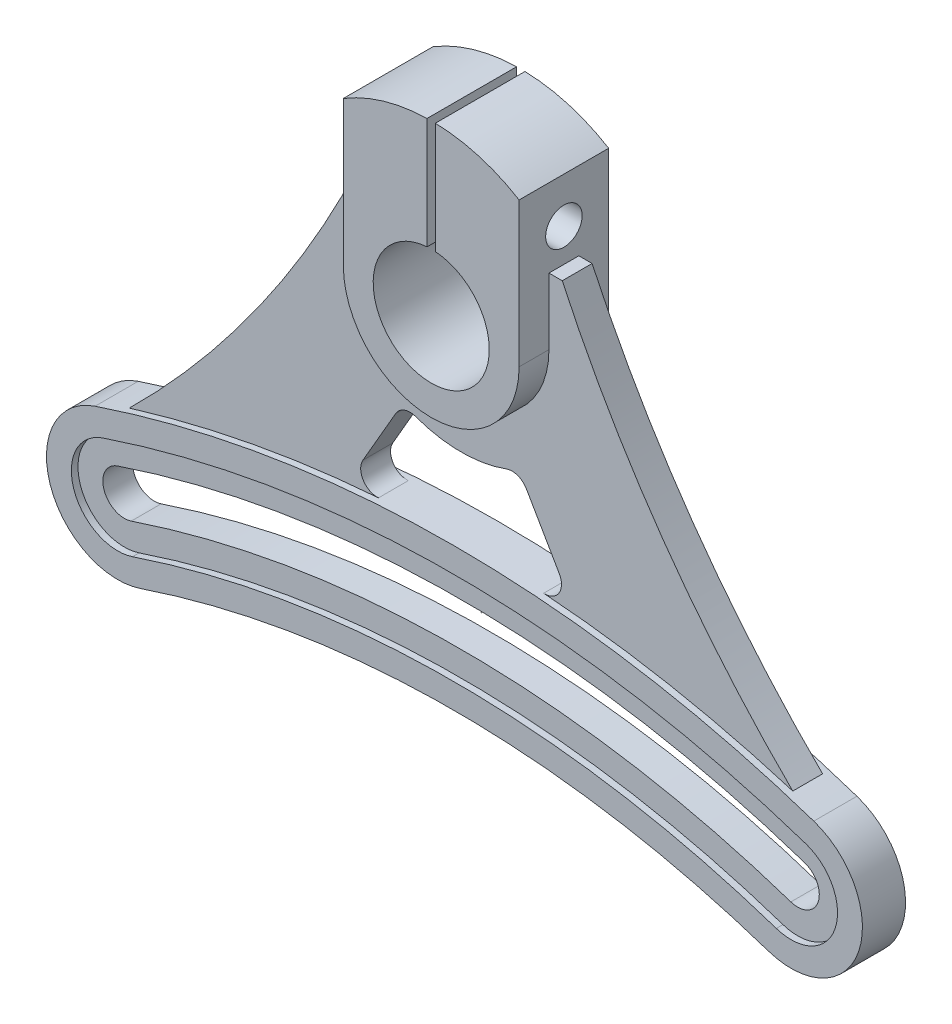
SolidWorks part; units mm, degrees
ref_plane "前视基准面" through (0, 0, 0) normal (0, 0, 1) x (1, 0, 0)
ref_plane "上视基准面" through (0, 0, 0) normal (0, 1, 0) x (1, 0, 0)
ref_plane "右视基准面" through (0, 0, 0) normal (1, 0, 0) x (0, 0, -1)
sketch "草图1" plane through (0, 0, 0) normal (0, 0, 1) x (1, 0, 0)
  line L0 (-26.5, 0) -> (-26.5, 43.5746)
  line L1 (26.5, 0) -> (26.5, 43.5746)
  circle A0 centre (0, 0) radius 17.5
  arc A1 (-26.5, 0) -> (26.5, 0) centre (0, 0) ccw
  arc A2 (26.5, 43.5746) -> (-26.5, 43.5746) centre (0, 0) ccw
  dimension "D1" = 35
  dimension "D2" = 102
  dimension "D3" = 53
extrude "凸台-拉伸1" add sketch "草图1" along normal mid plane 27
sketch "草图2" plane through (0, 0, 13.5) normal (0, 0, 1) x (1, 0, 0)
  line L0 (0, 0) -> (0, 70.8005) construction
  line L1 (-1.25, 64.567) -> (1.25, 64.567)
  line L2 (-1.25, 64.567) -> (-1.25, 8.1685)
  line L3 (-1.25, 8.1685) -> (1.25, 8.1685)
  line L4 (1.25, 64.567) -> (1.25, 8.1685)
  dimension "D1" = 2.5
extrude "切除-拉伸1" cut sketch "草图2" against normal through all
sketch "草图3" plane through (-26.5, 0, 0) normal (-1, 0, 0) x (0, 0, 1)
  line L0 (0, 50.9847) -> (0, 29.9847) construction
  line L1 (13.5, 50.9847) -> (-13.5, 50.9847) construction
  circle A0 centre (0, 29.9847) radius 5.5
  dimension "D2" = 11
  dimension "D1" = 21
extrude "切除-拉伸2" cut sketch "草图3" against normal through all
sketch "草图4" plane through (0, 0, 0) normal (0, 0, 1) x (1, 0, 0)
  line L0 (0, -106.5) -> (22.7411, -106.5) construction
  line L1 (-123, -101.5785) -> (-123, -58.0313) construction
  line L2 (123, -101.5785) -> (123, -67.6974) construction
  line L3 (0, 0) -> (0, -85) construction
  arc A0 (-101.5, -101.5785) -> (101.5, -101.5785) centre (0, -404) cw construction
  arc A1 (108.3409, -81.1959) -> (-108.3409, -81.1959) centre (0, -404) ccw
  arc A2 (94.6591, -121.9612) -> (-94.6591, -121.9612) centre (0, -404) ccw
  arc A3 (94.6591, -121.9612) -> (108.3409, -81.1959) centre (101.5, -101.5785) ccw
  arc A4 (-108.3409, -81.1959) -> (-94.6591, -121.9612) centre (-101.5, -101.5785) ccw
  point P3 (0, -85)
  dimension "D1" = 21.5
  dimension "D4" = 297.5
  dimension "D2" = 106.5
  dimension "D3" = 246
extrude "凸台-拉伸2" add sketch "草图4" along normal mid plane 13 separate body
sketch "草图5" plane through (0, 0, 6.5) normal (0, 0, 1) x (1, 0, 0)
  arc A0 (-101.5, -101.5785) -> (101.5, -101.5785) centre (0, -404) cw construction
  arc A1 (105.9545, -88.3061) -> (-105.9545, -88.3061) centre (0, -404) ccw
  arc A2 (97.0455, -114.8509) -> (-97.0455, -114.8509) centre (0, -404) ccw
  arc A3 (97.0455, -114.8509) -> (105.9545, -88.3061) centre (101.5, -101.5785) ccw
  arc A4 (-105.9545, -88.3061) -> (-97.0455, -114.8509) centre (-101.5, -101.5785) ccw
  arc A5 (-108.3409, -81.1959) -> (-94.6591, -121.9612) centre (-101.5, -101.5785) ccw construction
  arc A6 (94.6591, -121.9612) -> (108.3409, -81.1959) centre (101.5, -101.5785) ccw construction
  arc A7 (94.6591, -121.9612) -> (-94.6591, -121.9612) centre (0, -404) ccw construction
  point P3 (0, -85)
  dimension "D1" = 14
extrude "切除-拉伸3" cut sketch "草图5" against normal blind 2
mirror "镜向1" about plane through (0, 0, 0) normal (0, 0, 1) of "切除-拉伸3"
sketch "草图6" plane through (0, 0, 4.5) normal (0, 0, 1) x (1, 0, 0)
  arc A0 (-101.5, -101.5785) -> (101.5, -101.5785) centre (0, -404) cw construction
  arc A1 (103.5682, -95.4163) -> (-103.5682, -95.4163) centre (0, -404) ccw
  arc A2 (99.4318, -107.7407) -> (-99.4318, -107.7407) centre (0, -404) ccw
  arc A3 (99.4318, -107.7407) -> (103.5682, -95.4163) centre (101.5, -101.5785) ccw
  arc A4 (-103.5682, -95.4163) -> (-99.4318, -107.7407) centre (-101.5, -101.5785) ccw
  circle A5 centre (0, -85) radius 0.0005
  arc A6 (-108.3409, -81.1959) -> (-94.6591, -121.9612) centre (-101.5, -101.5785) ccw construction
  arc A7 (94.6591, -121.9612) -> (108.3409, -81.1959) centre (101.5, -101.5785) ccw construction
  arc A10 (94.6591, -121.9612) -> (-94.6591, -121.9612) centre (0, -404) ccw construction
  point P3 (0, -85)
  dimension "D1" = 6.5
  dimension "D2" = 0.001
extrude "切除-拉伸4" cut sketch "草图6" against normal through all
sketch "草图7" plane through (0, 0, 0) normal (0, 0, 1) x (1, 0, 0)
  line L0 (-26.5, 19.9847) -> (-30.5, 19.9847)
  line L2 (-26.5, 43.5746) -> (-26.5, 0) construction
  line L3 (-100, -78.5154) -> (-100, -66.5259) construction
  line L4 (0, 0) -> (0, 86.1313) construction
  line L5 (26.5, 19.9847) -> (30.5, 19.9847)
  line L6 (-26.5, 19.9847) -> (-26.5, 0)
  line L7 (26.5, 0) -> (26.5, 19.9847)
  line L8 (-17.5, -35.9687) -> (-34.4011, -65.2422)
  line L9 (17.5, -35.9687) -> (34.4011, -65.2422)
  arc A0 (-100, -78.5154) -> (-30.5, 19.9847) centre (-339.0729, 163.9396) ccw
  arc A2 (108.3409, -81.1959) -> (-108.3409, -81.1959) centre (0, -404) ccw construction
  arc A3 (100, -78.5154) -> (30.5, 19.9847) centre (339.0729, 163.9396) cw
  arc A4 (-26.5, 0) -> (26.5, 0) centre (0, 0) ccw
  arc A5 (100, -78.5154) -> (34.4011, -65.2422) centre (0, -404) ccw
  arc A6 (-17.5, -35.9687) -> (17.5, -35.9687) centre (0, 0) ccw
  arc A7 (-34.4011, -65.2422) -> (-100, -78.5154) centre (0, -404) ccw
  dimension "D2" = 681
  dimension "D5" = 80
  dimension "D1" = 31
  dimension "D3" = 4
  dimension "D4" = 100
  dimension "D6" = 60
  dimension "D7" = 35
extrude "凸台-拉伸3" add sketch "草图7" along normal mid plane 9
fillet "圆角1" radius 5 4 edges at (-34.4011, -65.2422, 0) (34.4011, -65.2422, 0) (17.5, -35.9687, 0) (-17.5, -35.9687, 0)
sketch "草图8" plane through (-26.5, 0, 0) normal (-1, 0, 0) x (0, 0, 1)
  line L0 (13.5, 43.5746) -> (-13.5, 43.5746) construction
  line L1 (5.1962, 38.9847) -> (-5.1962, 38.9847)
  line L2 (-5.1962, 38.9847) -> (-10.3923, 29.9847)
  line L3 (-10.3923, 29.9847) -> (-5.1962, 20.9847)
  line L4 (-5.1962, 20.9847) -> (5.1962, 20.9847)
  line L5 (5.1962, 20.9847) -> (10.3923, 29.9847)
  line L6 (10.3923, 29.9847) -> (5.1962, 38.9847)
  circle A0 centre (0, 29.9847) radius 9 construction
  dimension "D1" = 18
extrude "切除-拉伸5" cut sketch "草图8" against normal blind 10
